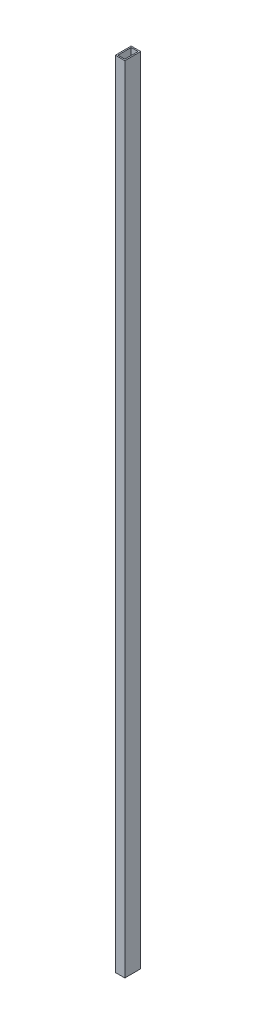
SolidWorks part; units mm, degrees
material "1.1181 (C35E)"
ref_plane "Спереди" through (0, 0, 0) normal (0, 0, 1) x (1, 0, 0)
ref_plane "Сверху" through (0, 0, 0) normal (0, 1, 0) x (1, 0, 0)
ref_plane "Справа" through (0, 0, 0) normal (1, 0, 0) x (0, 0, -1)
sketch "Эскиз1" plane through (0, 0, 0) normal (0, 1, 0) x (1, 0, 0)
  line L5 (-15, -25) -> (15, -25)
  line L6 (-15, -25) -> (-15, 25)
  line L11 (-15, 25) -> (15, 25)
  line L12 (15, -25) -> (15, 25)
  line L13 (-15, -25) -> (15, 25) construction
  line L14 (-15, 25) -> (15, -25) construction
  line L15 (-11, -21) -> (11, -21)
  line L16 (-11, -21) -> (-11, 21)
  line L17 (-11, 21) -> (11, 21)
  line L18 (11, -21) -> (11, 21)
  line L19 (-11, -21) -> (11, 21) construction
  line L20 (-11, 21) -> (11, -21) construction
  point P0 (0, 0)
  point P6 (0, 0)
  dimension "D1" = 30
  dimension "D2" = 50
  dimension "D3" = 4
  dimension "D4" = 4
extrude "Бобышка-Вытянуть1" add sketch "Эскиз1" along normal blind 2500
